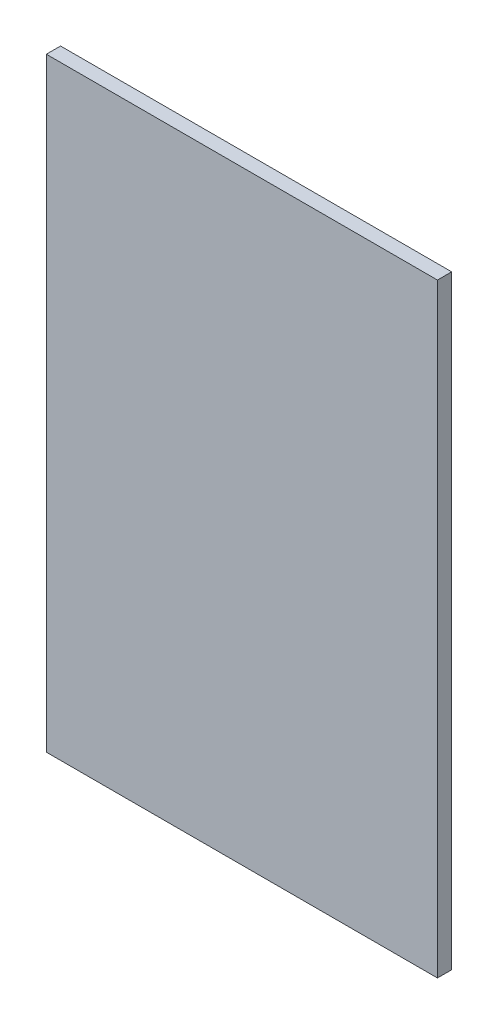
SolidWorks part; units mm, degrees
ref_plane "前视基准面" through (0, 0, 0) normal (0, 0, 1) x (1, 0, 0)
ref_plane "上视基准面" through (0, 0, 0) normal (0, 1, 0) x (1, 0, 0)
ref_plane "右视基准面" through (0, 0, 0) normal (1, 0, 0) x (0, 0, -1)
other "Configuration Table"
sketch "草图1" plane through (0, 0, 0) normal (0, 1, 0) x (1, 0, 0)
  line L1 (-9.7059, 7.8725) -> (100.2941, 7.8725)
  line L2 (-9.7059, 7.8725) -> (-9.7059, 3.8725)
  line L3 (-9.7059, 3.8725) -> (100.2941, 3.8725)
  line L4 (100.2941, 7.8725) -> (100.2941, 3.8725)
  point P4 (45.2941, 3.8725)
  dimension "D1" = 110
  dimension "D2" = 4
extrude "凸台-拉伸1" add sketch "草图1" along normal blind 170
